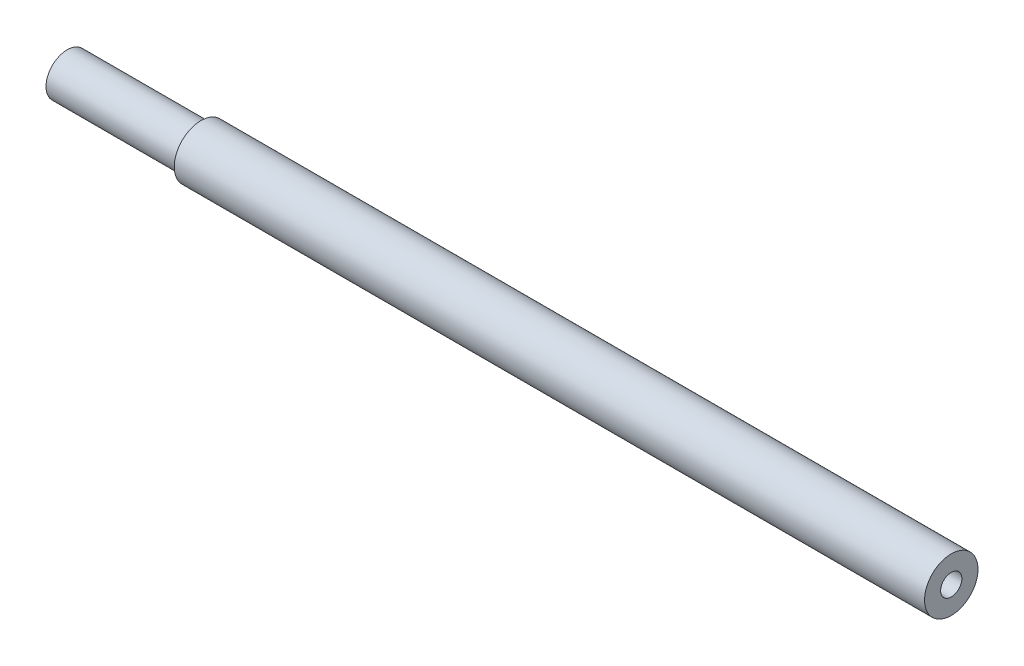
SolidWorks part; units mm, degrees
ref_plane "Front Plane" through (0, 0, 0) normal (0, 0, 1) x (1, 0, 0)
ref_plane "Top Plane" through (0, 0, 0) normal (0, 1, 0) x (1, 0, 0)
ref_plane "Right Plane" through (0, 0, 0) normal (1, 0, 0) x (0, 0, -1)
sketch "Sketch1" plane through (0, 0, 0) normal (1, 0, 0) x (0, 0, -1)
  circle A0 centre (0, 0) radius 2
  dimension "D1" = 4
extrude "Boss-Extrude1" add sketch "Sketch1" along normal mid plane 56.11
sketch "Sketch2" plane through (28.055, 0, 0) normal (1, 0, 0) x (0, 0, -1)
  circle A0 centre (0, 0) radius 0.795
  dimension "D1" = 1.59
extrude "Cut-Extrude1" cut sketch "Sketch2" against normal blind 7
sketch "Sketch3" plane through (-28.055, 0, 0) normal (-1, 0, 0) x (0, 0, 1)
  circle A0 centre (0, 0) radius 1.5875
  dimension "D1" = 3.175
extrude "Boss-Extrude2" add sketch "Sketch3" along normal blind 10
